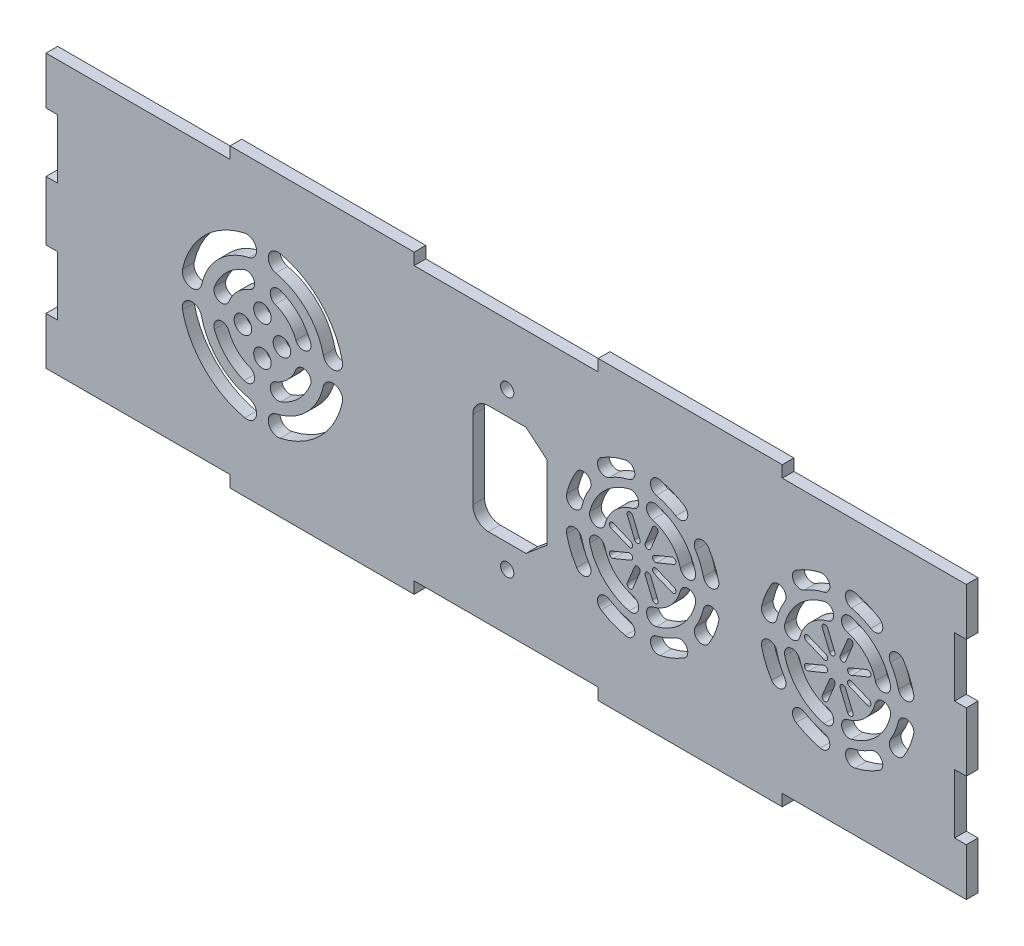
SolidWorks part; units mm, degrees
material "Pin"
ref_plane "Plan de face" through (0, 0, 0) normal (0, 0, 1) x (1, 0, 0)
ref_plane "Plan de dessus" through (0, 0, 0) normal (0, 1, 0) x (1, 0, 0)
ref_plane "Plan de droite" through (0, 0, 0) normal (1, 0, 0) x (0, 0, -1)
sketch "Esquisse1" plane through (0, 0, 0) normal (0, 0, 1) x (1, 0, 0)
  line L0 (-101.9585, 39.1998) -> (-57.7585, 39.1998)
  line L1 (-57.7585, 42.1998) -> (-10.5585, 42.1998)
  line L3 (-57.7585, -33.8002) -> (-10.5585, -33.8002)
  line L5 (128.0415, 26.9998) -> (128.0415, 11.7998)
  line L6 (-101.9585, -30.8002) -> (-57.7585, -30.8002)
  line L7 (-101.9585, 26.9998) -> (-101.9585, 11.7998)
  line L8 (-57.7585, 42.1998) -> (-57.7585, 39.1998)
  line L9 (-10.5585, -30.8002) -> (36.6415, -30.8002)
  line L10 (-10.5585, 42.1998) -> (-10.5585, 39.1998)
  line L11 (-104.9585, -33.8002) -> (131.0415, -33.8002) construction
  line L12 (36.6415, 42.1998) -> (36.6415, 39.1998)
  line L13 (36.6415, -33.8002) -> (83.8415, -33.8002)
  line L14 (83.8415, 42.1998) -> (83.8415, 39.1998)
  line L15 (-101.9585, -30.8002) -> (128.0415, -30.8002) construction
  line L16 (-104.9585, 26.9998) -> (-101.9585, 26.9998)
  line L17 (-104.9585, 11.7998) -> (-101.9585, 11.7998)
  line L18 (83.8415, -30.8002) -> (83.8415, -33.8002)
  line L19 (83.8415, -30.8002) -> (128.0415, -30.8002)
  line L20 (36.6415, -30.8002) -> (36.6415, -33.8002)
  line L21 (-104.9585, -33.8002) -> (-57.7585, -33.8002) construction
  line L22 (-10.5585, -30.8002) -> (-10.5585, -33.8002)
  line L23 (-57.7585, -30.8002) -> (-57.7585, -33.8002)
  line L24 (83.8415, -33.8002) -> (131.0415, -33.8002) construction
  line L25 (128.0415, 26.9998) -> (131.0415, 26.9998)
  line L26 (128.0415, 11.7998) -> (131.0415, 11.7998)
  line L27 (-104.9585, -3.4002) -> (-101.9585, -3.4002)
  line L28 (128.0415, -3.4002) -> (131.0415, -3.4002)
  line L29 (-104.9585, -18.6002) -> (-101.9585, -18.6002)
  line L30 (128.0415, -18.6002) -> (131.0415, -18.6002)
  line L31 (-104.9585, 26.9998) -> (-104.9585, 11.7998) construction
  line L32 (-34.1585, 47.9048) -> (-34.1585, 44.9048) [skipped]
  line L33 (13.0415, 47.9048) -> (13.0415, 44.9048) [skipped]
  line L34 (60.2415, 47.9048) -> (60.2415, 44.9048) [skipped]
  line L35 (-10.5585, 39.1998) -> (36.6415, 39.1998)
  line L36 (36.6415, 42.1998) -> (83.8415, 42.1998)
  line L37 (-101.9585, 39.1998) -> (128.0415, 39.1998) construction
  line L38 (83.8415, 39.1998) -> (128.0415, 39.1998)
  line L39 (-104.9585, 42.1998) -> (131.0415, 42.1998) construction
  line L40 (-57.7585, 42.1998) -> (-104.9585, 42.1998) construction
  line L41 (83.8415, 42.1998) -> (131.0415, 42.1998) construction
  line L42 (-104.9585, 11.7998) -> (-104.9585, -3.4002)
  line L43 (-101.9585, -3.4002) -> (-101.9585, -18.6002)
  line L44 (-104.9585, 42.1998) -> (-104.9585, -33.8002) construction
  line L46 (-101.9585, 39.1998) -> (-101.9585, -30.8002) construction
  line L47 (-101.9585, -30.8002) -> (-104.9585, -30.8002)
  line L48 (-104.9585, 42.1998) -> (-104.9585, 26.9998) construction
  line L49 (-104.9585, -18.6002) -> (-104.9585, -33.8002) construction
  line L50 (-104.9585, 26.9998) -> (-104.9585, 39.1998)
  line L51 (-104.9585, 39.1998) -> (-101.9585, 39.1998)
  line L52 (-104.9585, -30.8002) -> (-104.9585, -18.6002)
  line L53 (131.0415, 11.7998) -> (131.0415, -3.4002)
  line L54 (128.0415, 39.1998) -> (131.0415, 39.1998)
  line L55 (131.0415, 42.1998) -> (131.0415, -33.8002) construction
  line L56 (128.0415, -3.4002) -> (128.0415, -18.6002)
  line L57 (131.0415, 39.1998) -> (131.0415, 26.9998)
  line L58 (128.0415, 39.1998) -> (128.0415, -30.8002) construction
  line L59 (131.0415, -18.6002) -> (131.0415, -30.8002)
  line L60 (131.0415, -30.8002) -> (128.0415, -30.8002)
  line L61 (-104.9585, -33.8002) -> (131.0415, 42.1998) construction
  dimension "D1" = 236
  dimension "D2" = 76
  dimension "D3" = 3
  dimension "D4" = 7
  dimension "D6" = 4
extrude "Boss.-Extru.1" add sketch "Esquisse1" along normal blind 3
sketch "Esquisse2" plane through (0, 0, 3) normal (0, 0, 1) x (1, 0, 0)
  line L0 (-77.8548, 4.1998) -> (-49.4585, 4.1998) construction
  line L1 (-101.9585, 26.9998) -> (-101.9585, 11.7998) construction
  line L2 (-17.0754, 42.1998) -> (-17.0754, -33.8002) construction
  line L3 (-10.5585, 42.1998) -> (-57.7585, 42.1998) construction
  line L4 (-49.4585, -18.3002) -> (-49.4585, 26.6998) construction
  line L6 (-57.7585, -33.8002) -> (-10.5585, -33.8002) construction
  circle A0 centre (-49.4585, 4.1998) radius 22.5
  arc A1 (-53.9991, 24.703) -> (-69.9618, 8.7403) centre (-49.4585, 4.1998) ccw
  arc A2 (-52.918, 19.8213) -> (-65.0801, 7.6593) centre (-49.4585, 4.1998) ccw
  arc A4 (-45.4585, 22.2622) -> (-31.3961, 8.1998) centre (-49.4585, 4.1998) cw construction
  arc A5 (-28.9553, 8.7403) -> (-44.918, 24.703) centre (-49.4585, 4.1998) ccw
  arc A6 (-33.837, 7.6593) -> (-45.9991, 19.8213) centre (-49.4585, 4.1998) ccw
  arc A7 (-33.837, 7.6593) -> (-28.9553, 8.7403) centre (-31.3961, 8.1998) ccw
  arc A8 (-44.918, 24.703) -> (-45.9991, 19.8213) centre (-45.4585, 22.2622) ccw
  arc A9 (-31.3961, 0.1998) -> (-45.4585, -13.8626) centre (-49.4585, 4.1998) cw construction
  arc A10 (-44.918, -16.3035) -> (-28.9553, -0.3407) centre (-49.4585, 4.1998) ccw
  arc A11 (-45.9991, -11.4217) -> (-33.837, 0.7403) centre (-49.4585, 4.1998) ccw
  arc A12 (-45.9991, -11.4217) -> (-44.918, -16.3035) centre (-45.4585, -13.8626) ccw
  arc A13 (-28.9553, -0.3407) -> (-33.837, 0.7403) centre (-31.3961, 0.1998) ccw
  arc A14 (-53.4585, -13.8626) -> (-67.5209, 0.1998) centre (-49.4585, 4.1998) cw construction
  arc A15 (-69.9618, -0.3407) -> (-53.9991, -16.3035) centre (-49.4585, 4.1998) ccw
  arc A16 (-65.0801, 0.7403) -> (-52.918, -11.4217) centre (-49.4585, 4.1998) ccw
  arc A17 (-65.0801, 0.7403) -> (-69.9618, -0.3407) centre (-67.5209, 0.1998) ccw
  arc A18 (-53.9991, -16.3035) -> (-52.918, -11.4217) centre (-53.4585, -13.8626) ccw
  arc A19 (-67.5209, 8.1998) -> (-53.4585, 22.2622) centre (-49.4585, 4.1998) cw construction
  arc A22 (-52.918, 19.8213) -> (-53.9991, 24.703) centre (-53.4585, 22.2622) ccw
  arc A23 (-69.9618, 8.7403) -> (-65.0801, 7.6593) centre (-67.5209, 8.1998) ccw
  circle A24 centre (-49.4585, 9.1998) radius 2.25
  circle A25 centre (-44.4585, 4.1998) radius 2.25
  circle A26 centre (-49.4585, -0.8002) radius 2.25
  circle A27 centre (-54.4585, 4.1998) radius 2.25
  arc A36 (-45.4585, 14.6549) -> (-39.0035, 8.1998) centre (-49.4585, 4.1998) cw construction
  arc A37 (-37.1355, 8.9145) -> (-44.7439, 16.5228) centre (-49.4585, 4.1998) ccw
  arc A38 (-40.8714, 7.4851) -> (-46.1732, 12.7869) centre (-49.4585, 4.1998) ccw
  arc A39 (-40.8714, 7.4851) -> (-37.1355, 8.9145) centre (-39.0035, 8.1998) ccw
  arc A40 (-44.7439, 16.5228) -> (-46.1732, 12.7869) centre (-45.4585, 14.6549) ccw
  arc A42 (-39.0035, 0.1998) -> (-45.4585, -6.2553) centre (-49.4585, 4.1998) cw construction
  arc A43 (-44.7439, -8.1232) -> (-37.1355, -0.5149) centre (-49.4585, 4.1998) ccw
  arc A44 (-46.1732, -4.3873) -> (-40.8714, 0.9145) centre (-49.4585, 4.1998) ccw
  arc A45 (-46.1732, -4.3873) -> (-44.7439, -8.1232) centre (-45.4585, -6.2553) ccw
  arc A46 (-37.1355, -0.5149) -> (-40.8714, 0.9145) centre (-39.0035, 0.1998) ccw
  arc A47 (-53.4585, -6.2553) -> (-59.9136, 0.1998) centre (-49.4585, 4.1998) cw construction
  arc A48 (-61.7816, -0.5149) -> (-54.1732, -8.1232) centre (-49.4585, 4.1998) ccw
  arc A49 (-58.0457, 0.9145) -> (-52.7439, -4.3873) centre (-49.4585, 4.1998) ccw
  arc A50 (-58.0457, 0.9145) -> (-61.7816, -0.5149) centre (-59.9136, 0.1998) ccw
  arc A51 (-54.1732, -8.1232) -> (-52.7439, -4.3873) centre (-53.4585, -6.2553) ccw
  arc A52 (-59.9136, 8.1998) -> (-53.4585, 14.6549) centre (-49.4585, 4.1998) cw construction
  arc A53 (-54.1732, 16.5228) -> (-61.7816, 8.9145) centre (-49.4585, 4.1998) ccw
  arc A54 (-52.7439, 12.7869) -> (-58.0457, 7.4851) centre (-49.4585, 4.1998) ccw
  arc A55 (-52.7439, 12.7869) -> (-54.1732, 16.5228) centre (-53.4585, 14.6549) ccw
  arc A56 (-61.7816, 8.9145) -> (-58.0457, 7.4851) centre (-59.9136, 8.1998) ccw
  arc A92 (-67.5209, 8.1998) -> (-53.4585, 22.2622) centre (-49.4585, 4.1998) cw construction
  arc A93 (-53.9991, 24.703) -> (-69.9618, 8.7403) centre (-49.4585, 4.1998) ccw [skipped]
  arc A94 (-52.918, 19.8213) -> (-65.0801, 7.6593) centre (-49.4585, 4.1998) ccw [skipped]
  arc A95 (-52.918, 19.8213) -> (-53.9991, 24.703) centre (-53.4585, 22.2622) ccw [skipped]
  arc A96 (-69.9618, 8.7403) -> (-65.0801, 7.6593) centre (-67.5209, 8.1998) ccw [skipped]
  point P2 (-36.3771, 17.2813)
  point P9 (-49.4585, 4.1998)
  point P20 (-17.0754, 4.1998)
  point P23 (-31.7669, 9.6087)
  point P31 (-34.1577, 8.8777)
  point P32 (-36.3771, -8.8817)
  point P39 (-62.54, -8.8817)
  point P46 (-62.54, 17.2813)
  point P53 (-49.4585, 4.1998)
  point P60 (-49.4585, 4.1998)
  point P68 (-29.3761, 10.3396)
  point P74 (-41.5431, 12.1152)
  point P89 (-41.5431, -3.7156)
  point P96 (-57.374, -3.7156)
  point P105 (-57.374, 12.1152)
  point P112 (-49.4585, 4.1998)
  point P116 (-62.54, 17.2813)
  point P124 (-62.54, 17.2813)
  point P132 (-62.54, 17.2813)
  point P140 (-62.54, 17.2813)
  point P148 (-62.54, 17.2813)
  point P156 (-62.54, 17.2813)
  point P164 (-62.54, 17.2813)
  point P172 (-62.54, 17.2813)
  dimension "D1" = 45
  dimension "D6" = 4
  dimension "D5" = 4.5
  dimension "D4" = 5
  dimension "D7" = 52.5
  dimension "D2" = 4
  dimension "D9" = 4
  dimension "D10" = 4
  dimension "D12" = 2
  dimension "D14" = 5
  dimension "D3" = 13.0815
  dimension "D8" = 4
  dimension "D13" = 4
  dimension "D15" = 4
extrude "Enlèv. mat.-Extru.3" cut sketch "Esquisse2" against normal blind 10
sketch "Esquisse3" plane through (0, 0, 3) normal (0, 0, 1) x (1, 0, 0)
  line L8 (78.0415, 23.6374) -> (118.0415, 23.6374) construction
  line L9 (28.0415, 23.6374) -> (68.0415, 23.6374) construction
  line L11 (28.0415, 23.6374) -> (28.0415, -16.3626) construction
  line L13 (28.0415, -16.3626) -> (68.0415, -16.3626) construction
  line L14 (68.0415, 23.6374) -> (68.0415, -16.3626) construction
  line L16 (48.0415, 23.6374) -> (48.0415, -16.3626) construction
  line L17 (68.0415, 23.6374) -> (48.0415, 3.6374) construction
  line L18 (68.0415, 3.6374) -> (28.0415, 3.6374) construction
  line L19 (57.6227, 18.8755) -> (63.2796, 13.2186) construction
  line L20 (51.2695, 11.4307) -> (49.4056, 6.9307) construction
  line L21 (51.9624, 11.1437) -> (50.0985, 6.6437)
  line L22 (50.5766, 11.7177) -> (48.7127, 7.2177)
  line L23 (48.0415, 3.6374) -> (56.3257, 23.6374) construction
  line L24 (48.0415, 3.6374) -> (68.0415, 11.9217) construction
  line L26 (55.8372, 6.863) -> (51.3372, 4.999) construction
  line L27 (56.1242, 6.1701) -> (51.6242, 4.3061)
  line L28 (55.5502, 7.5559) -> (51.0502, 5.6919)
  line L29 (55.8372, 0.4033) -> (51.3372, 2.2672) construction
  line L30 (55.5502, -0.2896) -> (51.0502, 1.5743)
  line L31 (56.1242, 1.0962) -> (51.6242, 2.9602)
  line L32 (51.2695, -4.1644) -> (49.4056, 0.3356) construction
  line L33 (50.5766, -4.4514) -> (48.7127, 0.0486)
  line L34 (51.9624, -3.8774) -> (50.0985, 0.6226)
  line L35 (44.8098, -4.1644) -> (46.6738, 0.3356) construction
  line L36 (44.1169, -3.8774) -> (45.9809, 0.6226)
  line L37 (45.5028, -4.4514) -> (47.3667, 0.0486)
  line L38 (40.2421, 0.4033) -> (44.7421, 2.2672) construction
  line L39 (39.9551, 1.0962) -> (44.4551, 2.9602)
  line L40 (40.5292, -0.2896) -> (45.0292, 1.5743)
  line L41 (40.2421, 6.863) -> (44.7421, 4.999) construction
  line L42 (40.5292, 7.5559) -> (45.0292, 5.6919)
  line L43 (39.9551, 6.1701) -> (44.4551, 4.3061)
  line L44 (44.8098, 11.4307) -> (46.6738, 6.9307) construction
  line L45 (45.5028, 11.7177) -> (47.3667, 7.2177)
  line L46 (44.1169, 11.1437) -> (45.9809, 6.6437)
  line L47 (-69.3378, -16.3626) -> (-30.9516, -16.3626) construction
  line L48 (-69.3378, 24.7622) -> (-30.9516, 24.7622) construction
  line L51 (78.0415, -16.3626) -> (118.0415, -16.3626) construction
  line L52 (118.0415, 23.6374) -> (118.0415, -16.3626) construction
  line L53 (98.0415, 23.6374) -> (98.0415, -16.3626) construction
  line L54 (118.0415, 23.6374) -> (98.0415, 3.6374) construction
  line L55 (118.0415, 3.6374) -> (78.0415, 3.6374) construction
  line L56 (107.6227, 18.8755) -> (113.2796, 13.2186) construction
  line L63 (98.0415, 3.6374) -> (106.3257, 23.6374) construction
  line L72 (98.0415, 3.6374) -> (118.0415, 11.9217) construction
  line L87 (78.0415, 23.6374) -> (78.0415, -16.3626) construction
  line L96 (101.2695, 11.4307) -> (99.4056, 6.9307) construction
  line L99 (101.9624, 11.1437) -> (100.0985, 6.6437)
  line L102 (100.5766, 11.7177) -> (98.7127, 7.2177)
  line L105 (105.8372, 6.863) -> (101.3372, 4.999) construction
  line L108 (106.1242, 6.1701) -> (101.6242, 4.3061)
  line L111 (105.5502, 7.5559) -> (101.0502, 5.6919)
  line L114 (128.0415, -18.6002) -> (128.0415, -3.4002) construction
  line L115 (105.8372, 0.4033) -> (101.3372, 2.2672) construction
  line L116 (105.5502, -0.2896) -> (101.0502, 1.5743)
  line L117 (106.1242, 1.0962) -> (101.6242, 2.9602)
  line L118 (101.2695, -4.1644) -> (99.4056, 0.3356) construction
  line L119 (100.5766, -4.4514) -> (98.7127, 0.0486)
  line L120 (101.9624, -3.8774) -> (100.0985, 0.6226)
  line L121 (94.8098, -4.1644) -> (96.6738, 0.3356) construction
  line L122 (94.1169, -3.8774) -> (95.9809, 0.6226)
  line L123 (95.5028, -4.4514) -> (97.3667, 0.0486)
  line L124 (90.2421, 0.4033) -> (94.7421, 2.2672) construction
  line L125 (89.9551, 1.0962) -> (94.4551, 2.9602)
  line L126 (90.5292, -0.2896) -> (95.0292, 1.5743)
  line L127 (90.2421, 6.863) -> (94.7421, 4.999) construction
  line L128 (90.5292, 7.5559) -> (95.0292, 5.6919)
  line L129 (89.9551, 6.1701) -> (94.4551, 4.3061)
  line L130 (94.8098, 11.4307) -> (96.6738, 6.9307) construction
  line L131 (95.5028, 11.7177) -> (97.3667, 7.2177)
  line L132 (94.1169, 11.1437) -> (95.9809, 6.6437)
  circle A4 centre (48.0415, 3.6374) radius 20 construction
  arc A6 (57.6227, 18.8755) -> (52.0415, 21.1873) centre (48.0415, 3.6374) ccw construction
  arc A7 (58.6873, 20.5686) -> (52.4859, 23.1373) centre (48.0415, 3.6374) ccw
  arc A8 (56.5581, 17.1824) -> (51.597, 19.2373) centre (48.0415, 3.6374) ccw
  arc A9 (56.5581, 17.1824) -> (58.6873, 20.5686) centre (57.6227, 18.8755) ccw
  arc A10 (52.4859, 23.1373) -> (51.597, 19.2373) centre (52.0415, 21.1873) ccw
  arc A11 (65.5914, 7.6374) -> (63.2796, 13.2186) centre (48.0415, 3.6374) ccw construction
  arc A12 (67.5414, 8.0818) -> (64.9727, 14.2832) centre (48.0415, 3.6374) ccw
  arc A13 (63.6414, 7.193) -> (61.5864, 12.1541) centre (48.0415, 3.6374) ccw
  arc A14 (63.6414, 7.193) -> (67.5414, 8.0818) centre (65.5914, 7.6374) ccw
  arc A15 (64.9727, 14.2832) -> (61.5864, 12.1541) centre (63.2796, 13.2186) ccw
  arc A16 (66.0415, 3.6374) -> (48.0415, 21.6374) centre (48.0415, 3.6374) ccw construction
  arc A47 (60.0415, 3.6374) -> (48.0415, 15.6374) centre (48.0415, 3.6374) ccw construction
  arc A52 (51.0415, 15.2564) -> (59.6604, 6.6374) centre (48.0415, 3.6374) cw construction
  arc A69 (61.5969, 7.1374) -> (51.5415, 17.1928) centre (48.0415, 3.6374) ccw
  arc A70 (57.7239, 6.1374) -> (50.5415, 13.3199) centre (48.0415, 3.6374) ccw
  arc A71 (57.7239, 6.1374) -> (61.5969, 7.1374) centre (59.6604, 6.6374) ccw
  arc A72 (51.5415, 17.1928) -> (50.5415, 13.3199) centre (51.0415, 15.2564) ccw
  arc A73 (51.9624, 11.1437) -> (50.5766, 11.7177) centre (51.2695, 11.4307) ccw
  arc A74 (48.7127, 7.2177) -> (50.0985, 6.6437) centre (49.4056, 6.9307) ccw
  arc A75 (56.1242, 6.1701) -> (55.5502, 7.5559) centre (55.8372, 6.863) ccw
  arc A76 (51.0502, 5.6919) -> (51.6242, 4.3061) centre (51.3372, 4.999) ccw
  arc A77 (55.5502, -0.2896) -> (56.1242, 1.0962) centre (55.8372, 0.4033) ccw
  arc A78 (51.6242, 2.9602) -> (51.0502, 1.5743) centre (51.3372, 2.2672) ccw
  arc A79 (50.5766, -4.4514) -> (51.9624, -3.8774) centre (51.2695, -4.1644) ccw
  arc A80 (50.0985, 0.6226) -> (48.7127, 0.0486) centre (49.4056, 0.3356) ccw
  arc A81 (44.1169, -3.8774) -> (45.5028, -4.4514) centre (44.8098, -4.1644) ccw
  arc A82 (47.3667, 0.0486) -> (45.9809, 0.6226) centre (46.6738, 0.3356) ccw
  arc A83 (39.9551, 1.0962) -> (40.5292, -0.2896) centre (40.2421, 0.4033) ccw
  arc A84 (45.0292, 1.5743) -> (44.4551, 2.9602) centre (44.7421, 2.2672) ccw
  arc A85 (40.5292, 7.5559) -> (39.9551, 6.1701) centre (40.2421, 6.863) ccw
  arc A86 (44.4551, 4.3061) -> (45.0292, 5.6919) centre (44.7421, 4.999) ccw
  arc A87 (45.5028, 11.7177) -> (44.1169, 11.1437) centre (44.8098, 11.4307) ccw
  arc A88 (45.9809, 6.6437) -> (47.3667, 7.2177) centre (46.6738, 6.9307) ccw
  arc A89 (63.2796, -5.9438) -> (65.5914, -0.3626) centre (48.0415, 3.6374) ccw construction
  circle A90 centre (48.0415, 3.6374) radius 18 construction
  circle A91 centre (48.0415, 3.6374) radius 12 construction
  arc A96 (64.9727, -7.0084) -> (67.5414, -0.807) centre (48.0415, 3.6374) ccw
  arc A101 (61.5864, -4.8793) -> (63.6414, 0.0818) centre (48.0415, 3.6374) ccw
  arc A106 (61.5864, -4.8793) -> (64.9727, -7.0084) centre (63.2796, -5.9438) ccw
  arc A111 (67.5414, -0.807) -> (63.6414, 0.0818) centre (65.5914, -0.3626) ccw
  arc A116 (52.0415, -13.9125) -> (57.6227, -11.6007) centre (48.0415, 3.6374) ccw construction
  arc A121 (52.4859, -15.8625) -> (58.6873, -13.2938) centre (48.0415, 3.6374) ccw
  arc A126 (51.597, -11.9625) -> (56.5581, -9.9076) centre (48.0415, 3.6374) ccw
  arc A131 (51.597, -11.9625) -> (52.4859, -15.8625) centre (52.0415, -13.9125) ccw
  circle A136 centre (98.0415, 3.6374) radius 20 construction
  arc A205 (116.0415, 3.6374) -> (98.0415, 21.6374) centre (98.0415, 3.6374) ccw construction
  arc A234 (110.0415, 3.6374) -> (98.0415, 15.6374) centre (98.0415, 3.6374) ccw construction
  arc A239 (107.6227, 18.8755) -> (102.0415, 21.1873) centre (98.0415, 3.6374) ccw construction
  arc A264 (108.6873, 20.5686) -> (102.4859, 23.1373) centre (98.0415, 3.6374) ccw
  arc A279 (-52.918, 19.8213) -> (-53.9991, 24.703) centre (-53.4585, 22.2622) ccw construction
  arc A280 (-45.9991, -11.4217) -> (-44.918, -16.3035) centre (-45.4585, -13.8626) ccw construction
  arc A281 (58.6873, -13.2938) -> (56.5581, -9.9076) centre (57.6227, -11.6007) ccw
  arc A282 (59.6604, 0.6374) -> (51.0415, -7.9816) centre (48.0415, 3.6374) cw construction
  arc A283 (51.5415, -9.918) -> (61.5969, 0.1374) centre (48.0415, 3.6374) ccw
  arc A284 (50.5415, -6.0451) -> (57.7239, 1.1374) centre (48.0415, 3.6374) ccw
  arc A285 (50.5415, -6.0451) -> (51.5415, -9.918) centre (51.0415, -7.9816) ccw
  arc A286 (61.5969, 0.1374) -> (57.7239, 1.1374) centre (59.6604, 0.6374) ccw
  arc A287 (38.4602, -11.6007) -> (44.0415, -13.9125) centre (48.0415, 3.6374) ccw construction
  arc A288 (37.3956, -13.2938) -> (43.597, -15.8625) centre (48.0415, 3.6374) ccw
  arc A289 (39.5248, -9.9076) -> (44.4859, -11.9625) centre (48.0415, 3.6374) ccw
  arc A290 (39.5248, -9.9076) -> (37.3956, -13.2938) centre (38.4602, -11.6007) ccw
  arc A291 (43.597, -15.8625) -> (44.4859, -11.9625) centre (44.0415, -13.9125) ccw
  arc A292 (30.4915, -0.3626) -> (32.8034, -5.9438) centre (48.0415, 3.6374) ccw construction
  arc A293 (28.5415, -0.807) -> (31.1102, -7.0084) centre (48.0415, 3.6374) ccw
  arc A294 (32.4415, 0.0818) -> (34.4965, -4.8793) centre (48.0415, 3.6374) ccw
  arc A295 (32.4415, 0.0818) -> (28.5415, -0.807) centre (30.4915, -0.3626) ccw
  arc A296 (31.1102, -7.0084) -> (34.4965, -4.8793) centre (32.8034, -5.9438) ccw
  arc A297 (45.0415, -7.9816) -> (36.4225, 0.6374) centre (48.0415, 3.6374) cw construction
  arc A298 (34.486, 0.1374) -> (44.5415, -9.918) centre (48.0415, 3.6374) ccw
  arc A299 (38.359, 1.1374) -> (45.5415, -6.0451) centre (48.0415, 3.6374) ccw
  arc A300 (38.359, 1.1374) -> (34.486, 0.1374) centre (36.4225, 0.6374) ccw
  arc A301 (44.5415, -9.918) -> (45.5415, -6.0451) centre (45.0415, -7.9816) ccw
  arc A302 (32.8034, 13.2186) -> (30.4915, 7.6374) centre (48.0415, 3.6374) ccw construction
  arc A303 (31.1102, 14.2832) -> (28.5415, 8.0818) centre (48.0415, 3.6374) ccw
  arc A304 (34.4965, 12.1541) -> (32.4415, 7.193) centre (48.0415, 3.6374) ccw
  arc A305 (34.4965, 12.1541) -> (31.1102, 14.2832) centre (32.8034, 13.2186) ccw
  arc A306 (28.5415, 8.0818) -> (32.4415, 7.193) centre (30.4915, 7.6374) ccw
  arc A307 (44.0415, 21.1873) -> (38.4602, 18.8755) centre (48.0415, 3.6374) ccw construction
  arc A308 (43.597, 23.1373) -> (37.3956, 20.5686) centre (48.0415, 3.6374) ccw
  arc A309 (44.4859, 19.2373) -> (39.5248, 17.1824) centre (48.0415, 3.6374) ccw
  arc A310 (44.4859, 19.2373) -> (43.597, 23.1373) centre (44.0415, 21.1873) ccw
  arc A311 (37.3956, 20.5686) -> (39.5248, 17.1824) centre (38.4602, 18.8755) ccw
  arc A312 (36.4225, 6.6374) -> (45.0415, 15.2564) centre (48.0415, 3.6374) cw construction
  arc A313 (44.5415, 17.1928) -> (34.486, 7.1374) centre (48.0415, 3.6374) ccw
  arc A314 (45.5415, 13.3199) -> (38.359, 6.1374) centre (48.0415, 3.6374) ccw
  arc A315 (45.5415, 13.3199) -> (44.5415, 17.1928) centre (45.0415, 15.2564) ccw
  arc A316 (34.486, 7.1374) -> (38.359, 6.1374) centre (36.4225, 6.6374) ccw
  arc A333 (106.5581, 17.1824) -> (101.597, 19.2373) centre (98.0415, 3.6374) ccw
  arc A386 (106.5581, 17.1824) -> (108.6873, 20.5686) centre (107.6227, 18.8755) ccw
  arc A391 (102.4859, 23.1373) -> (101.597, 19.2373) centre (102.0415, 21.1873) ccw
  arc A396 (115.5914, 7.6374) -> (113.2796, 13.2186) centre (98.0415, 3.6374) ccw construction
  arc A401 (117.5414, 8.0818) -> (114.9727, 14.2832) centre (98.0415, 3.6374) ccw
  arc A406 (113.6414, 7.193) -> (111.5864, 12.1541) centre (98.0415, 3.6374) ccw
  arc A411 (113.6414, 7.193) -> (117.5414, 8.0818) centre (115.5914, 7.6374) ccw
  arc A416 (114.9727, 14.2832) -> (111.5864, 12.1541) centre (113.2796, 13.2186) ccw
  arc A421 (101.0415, 15.2564) -> (109.6604, 6.6374) centre (98.0415, 3.6374) cw construction
  arc A426 (111.5969, 7.1374) -> (101.5415, 17.1928) centre (98.0415, 3.6374) ccw
  arc A431 (107.7239, 6.1374) -> (100.5415, 13.3199) centre (98.0415, 3.6374) ccw
  arc A432 (107.7239, 6.1374) -> (111.5969, 7.1374) centre (109.6604, 6.6374) ccw
  arc A433 (101.5415, 17.1928) -> (100.5415, 13.3199) centre (101.0415, 15.2564) ccw
  arc A434 (101.9624, 11.1437) -> (100.5766, 11.7177) centre (101.2695, 11.4307) ccw
  arc A435 (98.7127, 7.2177) -> (100.0985, 6.6437) centre (99.4056, 6.9307) ccw
  arc A436 (106.1242, 6.1701) -> (105.5502, 7.5559) centre (105.8372, 6.863) ccw
  arc A437 (101.0502, 5.6919) -> (101.6242, 4.3061) centre (101.3372, 4.999) ccw
  arc A438 (105.5502, -0.2896) -> (106.1242, 1.0962) centre (105.8372, 0.4033) ccw
  arc A439 (101.6242, 2.9602) -> (101.0502, 1.5743) centre (101.3372, 2.2672) ccw
  arc A440 (100.5766, -4.4514) -> (101.9624, -3.8774) centre (101.2695, -4.1644) ccw
  arc A441 (100.0985, 0.6226) -> (98.7127, 0.0486) centre (99.4056, 0.3356) ccw
  arc A442 (94.1169, -3.8774) -> (95.5028, -4.4514) centre (94.8098, -4.1644) ccw
  arc A443 (97.3667, 0.0486) -> (95.9809, 0.6226) centre (96.6738, 0.3356) ccw
  arc A444 (89.9551, 1.0962) -> (90.5292, -0.2896) centre (90.2421, 0.4033) ccw
  arc A445 (95.0292, 1.5743) -> (94.4551, 2.9602) centre (94.7421, 2.2672) ccw
  arc A446 (90.5292, 7.5559) -> (89.9551, 6.1701) centre (90.2421, 6.863) ccw
  arc A447 (94.4551, 4.3061) -> (95.0292, 5.6919) centre (94.7421, 4.999) ccw
  arc A448 (95.5028, 11.7177) -> (94.1169, 11.1437) centre (94.8098, 11.4307) ccw
  arc A449 (95.9809, 6.6437) -> (97.3667, 7.2177) centre (96.6738, 6.9307) ccw
  arc A450 (113.2796, -5.9438) -> (115.5914, -0.3626) centre (98.0415, 3.6374) ccw construction
  arc A451 (114.9727, -7.0084) -> (117.5414, -0.807) centre (98.0415, 3.6374) ccw
  arc A452 (111.5864, -4.8793) -> (113.6414, 0.0818) centre (98.0415, 3.6374) ccw
  arc A453 (111.5864, -4.8793) -> (114.9727, -7.0084) centre (113.2796, -5.9438) ccw
  arc A454 (117.5414, -0.807) -> (113.6414, 0.0818) centre (115.5914, -0.3626) ccw
  arc A455 (102.0415, -13.9125) -> (107.6227, -11.6007) centre (98.0415, 3.6374) ccw construction
  arc A456 (102.4859, -15.8625) -> (108.6873, -13.2938) centre (98.0415, 3.6374) ccw
  arc A457 (101.597, -11.9625) -> (106.5581, -9.9076) centre (98.0415, 3.6374) ccw
  arc A458 (101.597, -11.9625) -> (102.4859, -15.8625) centre (102.0415, -13.9125) ccw
  arc A459 (108.6873, -13.2938) -> (106.5581, -9.9076) centre (107.6227, -11.6007) ccw
  arc A460 (109.6604, 0.6374) -> (101.0415, -7.9816) centre (98.0415, 3.6374) cw construction
  arc A461 (101.5415, -9.918) -> (111.5969, 0.1374) centre (98.0415, 3.6374) ccw
  arc A462 (100.5415, -6.0451) -> (107.7239, 1.1374) centre (98.0415, 3.6374) ccw
  arc A463 (100.5415, -6.0451) -> (101.5415, -9.918) centre (101.0415, -7.9816) ccw
  arc A464 (111.5969, 0.1374) -> (107.7239, 1.1374) centre (109.6604, 0.6374) ccw
  arc A465 (88.4602, -11.6007) -> (94.0415, -13.9125) centre (98.0415, 3.6374) ccw construction
  arc A466 (87.3956, -13.2938) -> (93.597, -15.8625) centre (98.0415, 3.6374) ccw
  arc A467 (89.5248, -9.9076) -> (94.4859, -11.9625) centre (98.0415, 3.6374) ccw
  arc A468 (89.5248, -9.9076) -> (87.3956, -13.2938) centre (88.4602, -11.6007) ccw
  arc A469 (93.597, -15.8625) -> (94.4859, -11.9625) centre (94.0415, -13.9125) ccw
  arc A470 (80.4915, -0.3626) -> (82.8034, -5.9438) centre (98.0415, 3.6374) ccw construction
  arc A471 (78.5415, -0.807) -> (81.1102, -7.0084) centre (98.0415, 3.6374) ccw
  arc A472 (82.4415, 0.0818) -> (84.4965, -4.8793) centre (98.0415, 3.6374) ccw
  arc A473 (82.4415, 0.0818) -> (78.5415, -0.807) centre (80.4915, -0.3626) ccw
  arc A474 (81.1102, -7.0084) -> (84.4965, -4.8793) centre (82.8034, -5.9438) ccw
  arc A475 (95.0415, -7.9816) -> (86.4225, 0.6374) centre (98.0415, 3.6374) cw construction
  arc A476 (84.486, 0.1374) -> (94.5415, -9.918) centre (98.0415, 3.6374) ccw
  arc A477 (88.359, 1.1374) -> (95.5415, -6.0451) centre (98.0415, 3.6374) ccw
  arc A478 (88.359, 1.1374) -> (84.486, 0.1374) centre (86.4225, 0.6374) ccw
  arc A479 (94.5415, -9.918) -> (95.5415, -6.0451) centre (95.0415, -7.9816) ccw
  arc A480 (82.8034, 13.2186) -> (80.4915, 7.6374) centre (98.0415, 3.6374) ccw construction
  arc A481 (81.1102, 14.2832) -> (78.5415, 8.0818) centre (98.0415, 3.6374) ccw
  arc A482 (84.4965, 12.1541) -> (82.4415, 7.193) centre (98.0415, 3.6374) ccw
  arc A483 (84.4965, 12.1541) -> (81.1102, 14.2832) centre (82.8034, 13.2186) ccw
  arc A484 (78.5415, 8.0818) -> (82.4415, 7.193) centre (80.4915, 7.6374) ccw
  arc A485 (94.0415, 21.1873) -> (88.4602, 18.8755) centre (98.0415, 3.6374) ccw construction
  arc A486 (93.597, 23.1373) -> (87.3956, 20.5686) centre (98.0415, 3.6374) ccw
  arc A487 (94.4859, 19.2373) -> (89.5248, 17.1824) centre (98.0415, 3.6374) ccw
  arc A488 (94.4859, 19.2373) -> (93.597, 23.1373) centre (94.0415, 21.1873) ccw
  arc A489 (87.3956, 20.5686) -> (89.5248, 17.1824) centre (88.4602, 18.8755) ccw
  arc A490 (86.4225, 6.6374) -> (95.0415, 15.2564) centre (98.0415, 3.6374) cw construction
  arc A491 (94.5415, 17.1928) -> (84.486, 7.1374) centre (98.0415, 3.6374) ccw
  arc A492 (95.5415, 13.3199) -> (88.359, 6.1374) centre (98.0415, 3.6374) ccw
  arc A493 (95.5415, 13.3199) -> (94.5415, 17.1928) centre (95.0415, 15.2564) ccw
  arc A494 (84.486, 7.1374) -> (88.359, 6.1374) centre (86.4225, 6.6374) ccw
  point P11 (48.0415, 23.6374)
  point P12 (28.0415, 3.6374)
  point P13 (34.4192, 11.7658)
  point P21 (54.9298, 20.2672)
  point P26 (60.4511, 16.0471)
  point P30 (64.6713, 10.5257)
  point P35 (34.4192, 11.7658)
  point P38 (46.4192, 11.7658)
  point P43 (56.5267, 12.1227)
  point P50 (50.3376, 9.1807)
  point P60 (53.5872, 5.931)
  point P61 (34.4192, 11.7658)
  point P64 (52.4192, 11.7658)
  point P71 (53.5872, 1.3353)
  point P78 (50.3376, -1.9144)
  point P82 (34.4192, 11.7658)
  point P86 (45.7418, -1.9144)
  point P90 (51.6327, 17.0285)
  point P94 (42.4921, 1.3353)
  point P101 (42.4921, 5.931)
  point P108 (45.7418, 9.1807)
  point P113 (48.0397, 3.6331)
  point P114 (34.4192, 11.7658)
  point P115 (45.4167, 15.1281)
  point P121 (64.6713, -3.2509)
  point P130 (54.9298, -12.9924)
  point P137 (56.5267, -4.8479)
  point P142 (34.4192, 11.7658)
  point P145 (41.1532, -12.9924)
  point P152 (31.4116, -3.2509)
  point P159 (39.5562, -4.8479)
  point P166 (31.4116, 10.5257)
  point P175 (41.1532, 20.2672)
  point P182 (39.5562, 12.1227)
  point P198 (104.9298, 20.2672)
  point P206 (114.6713, 10.5257)
  point P217 (106.5267, 12.1227)
  point P224 (100.3376, 9.1807)
  point P236 (103.5872, 5.931)
  point P237 (84.4192, 11.7658)
  point P245 (103.5872, 1.3353)
  point P252 (100.3376, -1.9144)
  point P256 (84.4192, 11.7658)
  point P260 (95.7418, -1.9144)
  point P267 (92.4921, 1.3353)
  point P274 (92.4921, 5.931)
  point P281 (95.7418, 9.1807)
  point P286 (98.0397, 3.6331)
  point P287 (84.4192, 11.7658)
  point P292 (114.6713, -3.2509)
  point P299 (104.9298, -12.9924)
  point P306 (106.5267, -4.8479)
  point P311 (84.4192, 11.7658)
  point P314 (91.1532, -12.9924)
  point P321 (81.4116, -3.2509)
  point P328 (89.5562, -4.8479)
  point P335 (81.4116, 10.5257)
  point P342 (91.1532, 20.2672)
  point P349 (89.5562, 12.1227)
  point P361 (34.4192, 3.6374)
  point P363 (84.4192, 3.6374)
  dimension "D5" = 2
  dimension "D13" = 22.5
  dimension "D14" = 22.5
  dimension "D12" = 4
  dimension "D20" = 4
  dimension "D3" = 16
  dimension "D24" = 14
  dimension "D19" = 12
  dimension "D1" = 40
  dimension "D2" = 40
  dimension "D4" = 60
  dimension "D6" = 4
  dimension "D7" = 4
  dimension "D8" = 8
  dimension "D11" = 3
  dimension "D9" = 3
  dimension "D15" = 1.5
  dimension "D16" = 4.5
  dimension "D17" = 6
  dimension "D10" = 2
  dimension "D18" = 8
extrude "Enlèv. mat.-Extru.4" cut sketch "Esquisse3" along direction (0, 0, -1) on the side against the normal blind 10
hole_wizard "Diamètre du perçage Ø2.5 (2.5)1" positions "Esquisse4" profile "Esquisse5" hole size "Ø2.5" standard "Ansi Metric"
sketch "Esquisse4" plane through (0, 0, 0) normal (0, 0, -1) x (-1, 0, 0)
  point P8 (-64.7226, -12.5249)
  point P10 (-64.7226, 19.4751)
  point P12 (-32.7226, 19.4751)
  point P14 (-32.7226, -12.5249)
  point P19 (-82.7226, -12.5249)
  point P22 (-82.7226, 19.4751)
  point P25 (-114.7226, 19.4751)
  point P32 (-114.7226, -12.5249)
sketch "Esquisse5" plane through (64.7226, -12.5249, 0) normal (1, 0, 0) x (0, 1, 0)
  line L0 (0, 0) -> (0, 2.7511)
  line L1 (0, 2.7511) -> (1.25, 2)
  line L2 (1.25, 2) -> (1.25, 0)
  line L5 (1.25, 0) -> (0, 0)
  line L10 (0, 2.7511) -> (-1.25, 2) construction
  line L11 (0, -6.35) -> (0, 107.95) construction
  dimension "Diamètre du perçage" = 2.5
  dimension "Profondeur du perçage" = 2
  dimension "Angle de pointe" = 118
sketch "Esquisse6" plane through (0, 0, 0) normal (0, 0, -1) x (-1, 0, 0)
  line L6 (-59.6282, 23.1873) -> (-28.4915, 23.1873) construction
  line L7 (-28.4915, 23.1873) -> (-28.4915, -15.9125) construction
  line L8 (-28.4915, -15.9125) -> (-59.6282, -15.9125) construction
  line L9 (35.2071, -16.3626) -> (65.5601, -16.3626) construction
  line L10 (-13.3101, 23.6374) -> (-13.3101, 17.6374) construction
  line L11 (-13.3101, -10.3626) -> (-13.3101, -16.3626) construction
  line L12 (28.8961, 13.0244) -> (28.8961, -12.3626) construction
  line L13 (-23.4915, -5.8626) -> (-23.4915, 13.1374)
  line L14 (-23.4915, 13.1374) -> (-18.1286, 17.6374)
  line L15 (-18.1286, 17.6374) -> (-8.4915, 17.6374)
  line L16 (-4.4915, 13.6374) -> (-4.4915, -6.3626)
  line L17 (-8.4915, -10.3626) -> (-18.1286, -10.3626)
  line L18 (-18.1286, -10.3626) -> (-23.4915, -5.8626)
  arc A4 (28.9553, 8.7403) -> (33.837, 7.6593) centre (31.3961, 8.1998) ccw construction
  arc A5 (52.918, -11.4217) -> (53.9991, -16.3035) centre (53.4585, -13.8626) ccw construction
  arc A11 (-4.4915, -6.3626) -> (-8.4915, -10.3626) centre (-8.4915, -6.3626) cw
  arc A12 (-8.4915, 17.6374) -> (-4.4915, 13.6374) centre (-8.4915, 13.6374) cw
  arc A13 (-44.4859, -11.9625) -> (-43.597, -15.8625) centre (-44.0415, -13.9125) ccw construction
  arc A14 (-43.597, 23.1373) -> (-44.4859, 19.2373) centre (-44.0415, 21.1873) ccw construction
  circle A15 centre (-13.3101, 23.6374) radius 1.7
  circle A16 centre (-13.3101, -16.3626) radius 1.7
  arc A17 (-28.5415, -0.807) -> (-32.4415, 0.0818) centre (-30.4915, -0.3626) ccw construction
  point P10 (-23.4915, 3.6374)
  point P11 (-4.4915, 3.6374)
  point P12 (-28.4915, 3.6374)
  point P34 (-13.3101, 17.6374)
  dimension "D3" = 40
  dimension "D2" = 4
  dimension "D4" = 3.4
  dimension "D5" = 5
  dimension "D10" = 28
  dimension "D11" = 19
  dimension "D12" = 19
  dimension "D13" = 40
extrude "Enlèv. mat.-Extru.6" cut sketch "Esquisse6" against normal up to next
